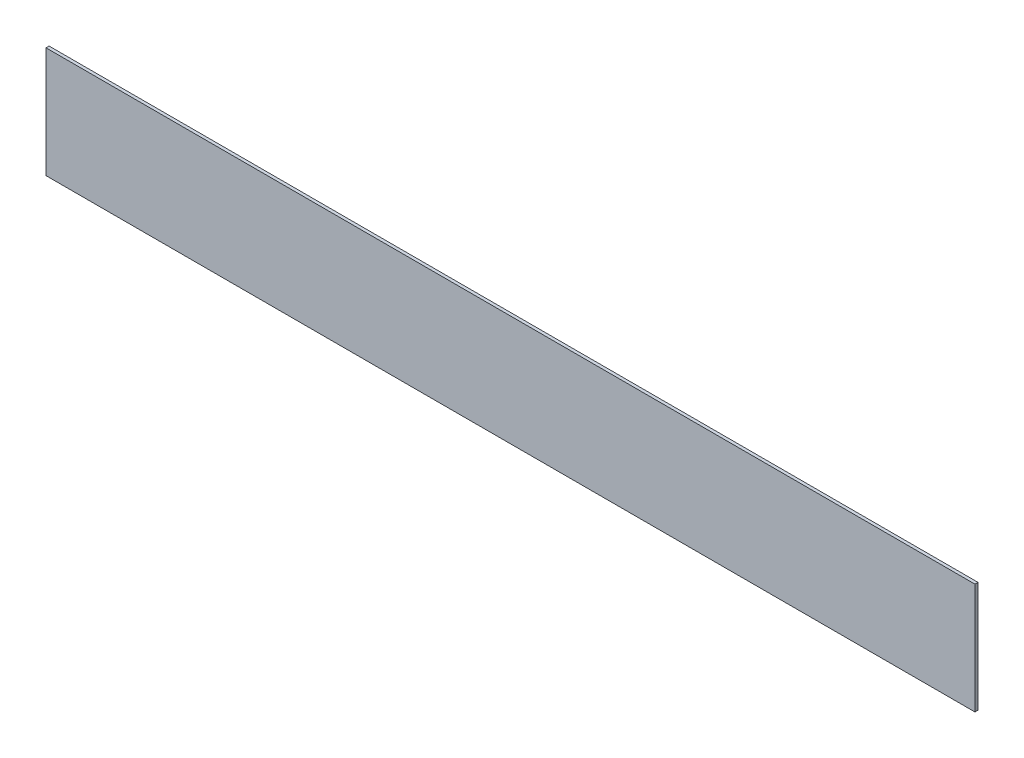
SolidWorks part; units mm, degrees
ref_plane "Front Plane" through (0, 0, 0) normal (0, 0, 1) x (1, 0, 0)
ref_plane "Top Plane" through (0, 0, 0) normal (0, 1, 0) x (1, 0, 0)
ref_plane "Right Plane" through (0, 0, 0) normal (1, 0, 0) x (0, 0, -1)
other "Configuration Table"
sketch "Sketch1" plane through (0, 0, 0) normal (0, 0, 1) x (1, 0, 0)
  line L1 (158, 249) -> (460, 249)
  line L2 (158, 249) -> (158, 285)
  line L3 (158, 285) -> (460, 285)
  line L4 (460, 249) -> (460, 285)
extrude "CEK_1L_kulp_cukuru_1.0_1" add sketch "Sketch1" along normal blind 1 from offset 26 separate body
